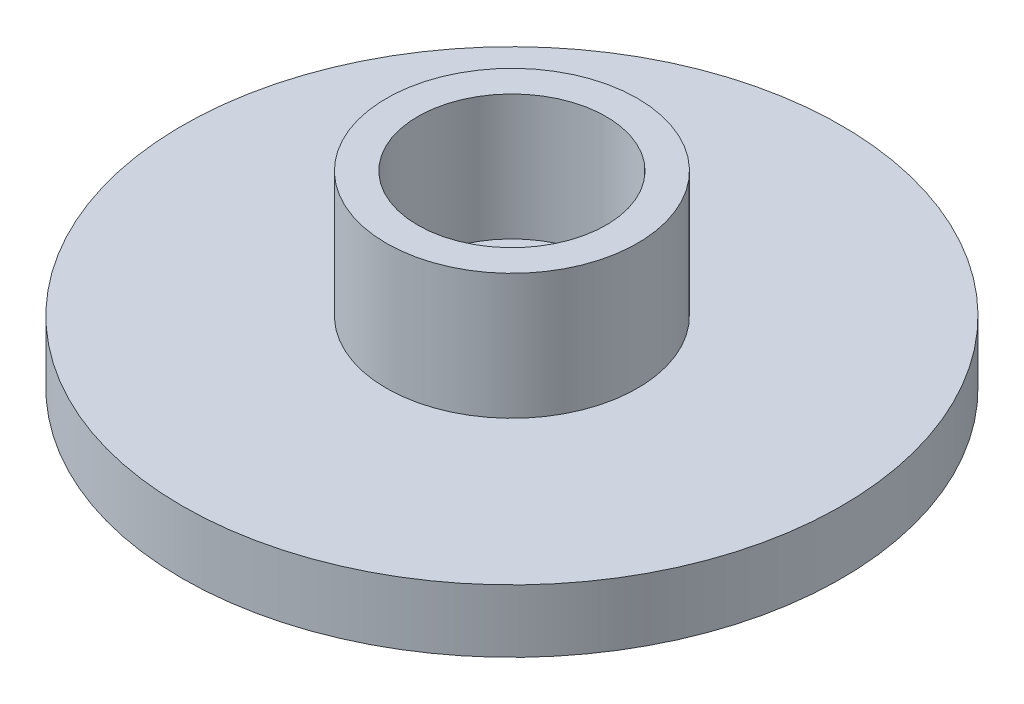
SolidWorks part; units mm, degrees
ref_plane "Front Plane" through (0, 0, 0) normal (0, 0, 1) x (1, 0, 0)
ref_plane "Top Plane" through (0, 0, 0) normal (0, 1, 0) x (1, 0, 0)
ref_plane "Right Plane" through (0, 0, 0) normal (1, 0, 0) x (0, 0, -1)
sketch "Sketch1" plane through (0, 0, 0) normal (0, 1, 0) x (1, 0, 0)
  circle A0 centre (0, 0) radius 10.5
  dimension "D1" = 21
extrude "Boss-Extrude1" add sketch "Sketch1" along normal blind 2
sketch "Sketch2" plane through (0, 2, 0) normal (0, 1, 0) x (1, 0, 0)
  circle A0 centre (0, 0) radius 4
  dimension "D1" = 8
extrude "Boss-Extrude2" add sketch "Sketch2" along normal blind 4
sketch "Sketch3" plane through (0, 6, 0) normal (0, 1, 0) x (1, 0, 0)
  circle A0 centre (0, 0) radius 3
  dimension "D1" = 6
extrude "Cut-Extrude1" cut sketch "Sketch3" against normal blind 4
